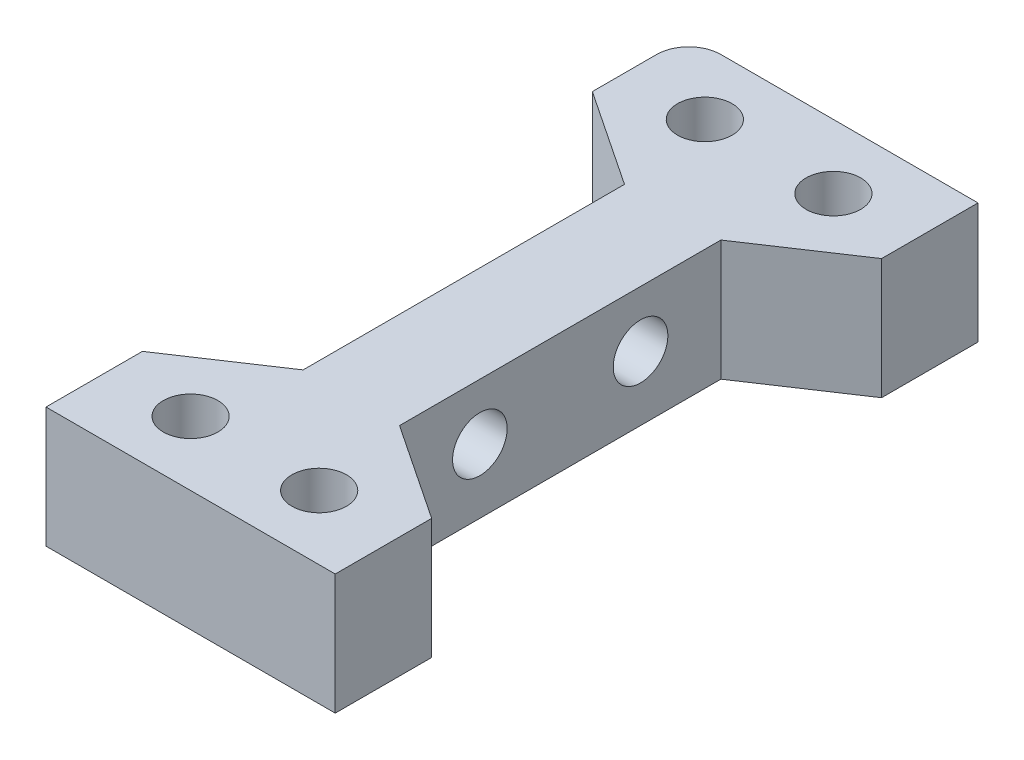
SolidWorks part; units mm, degrees
ref_plane "Front Plane" through (0, 0, 0) normal (0, 0, 1) x (1, 0, 0)
ref_plane "Top Plane" through (0, 0, 0) normal (0, 1, 0) x (1, 0, 0)
ref_plane "Right Plane" through (0, 0, 0) normal (1, 0, 0) x (0, 0, -1)
sketch "Sketch1" plane through (0, 0, 0) normal (0, 1, 0) x (1, 0, 0)
  line L0 (-3, 10) -> (-9, 14)
  line L1 (-3, -10) -> (3, -10)
  line L2 (-3, -10) -> (-3, 10)
  line L3 (-3, 10) -> (3, 10)
  line L4 (3, -10) -> (3, 10)
  line L5 (-3, -10) -> (3, 10) construction
  line L6 (-3, 10) -> (3, -10) construction
  line L7 (-9, 14) -> (-9, 20)
  line L8 (-9, 20) -> (9, 20)
  line L9 (9, 20) -> (9, 14)
  line L10 (9, 14) -> (3, 10)
  line L11 (0, 0) -> (9, 0) construction
  line L12 (9, -14) -> (3, -10)
  line L13 (9, -20) -> (9, -14)
  line L14 (-9, -20) -> (9, -20)
  line L15 (-9, -14) -> (-9, -20)
  line L16 (-3, -10) -> (3, -10)
  line L17 (-3, -10) -> (-9, -14)
  circle A0 centre (-4, 16) radius 1.7
  circle A1 centre (4, 16) radius 1.7
  circle A2 centre (4, -16) radius 1.7
  circle A3 centre (-4, -16) radius 1.7
  point P0 (0, 0)
  dimension "D8" = 3.4
  dimension "D9" = 3.4
  dimension "D1" = 6
  dimension "D2" = 20
  dimension "D3" = 4
  dimension "D4" = 4
  dimension "D5" = 6
  dimension "D6" = 6
  dimension "D7" = 6
  dimension "D10" = 8
  dimension "D11" = 4
  dimension "D12" = 4
extrude "Boss-Extrude1" add sketch "Sketch1" along normal blind 7.5 contours L1 L17 L15 L14 L13 L12 A2 A3 | L1 L4 L3 L2 | L10 L9 L8 L7 L0 L3 A1 A0
sketch "Sketch2" plane through (0, 7.5, 0) normal (0, 1, 0) x (1, 0, 0)
  line L0 (-3, 10) -> (3, 10)
  line L1 (-3, -10) -> (3, -10)
  line L12 (9, -14) -> (3, -10)
  line L13 (3, -10) -> (3, 10)
  line L14 (3, 10) -> (9, 14)
  line L15 (9, 14) -> (9, 20)
  line L16 (9, 20) -> (-9, 20)
  line L17 (-9, 20) -> (-9, 14)
  line L18 (-9, 14) -> (-3, 10)
  line L19 (-3, 10) -> (-3, -10)
  line L20 (-3, -10) -> (-9, -14)
  line L21 (-9, -14) -> (-9, -20)
  line L22 (-9, -20) -> (9, -20)
  line L23 (9, -20) -> (9, -14)
  line L24 (9, -14) -> (3, -10)
  line L25 (3, -10) -> (3, 10)
  line L26 (3, 10) -> (9, 14)
  line L27 (9, 14) -> (9, 20)
  line L28 (9, 20) -> (-9, 20)
  line L29 (-9, 20) -> (-9, 14)
  line L30 (-9, 14) -> (-3, 10)
  line L31 (-3, 10) -> (-3, -10)
  line L32 (-3, -10) -> (-9, -14)
  line L33 (-9, -14) -> (-9, -20)
  line L34 (-9, -20) -> (9, -20)
  line L35 (9, -20) -> (9, -14)
  circle M13 centre (4, -16) radius 1.7
  line M14 (9, -14) -> (3, -10)
  line M16 (3, 10) -> (9, 14)
  line M17 (9, 14) -> (9, 20)
  line M18 (9, 20) -> (-9, 20)
  line M19 (-9, 20) -> (-9, 14)
  line M20 (-9, 14) -> (-3, 10)
  line M22 (-3, -10) -> (-9, -14)
  line M23 (-9, -14) -> (-9, -20)
  line M24 (-9, -20) -> (9, -20)
  line M25 (9, -20) -> (9, -14)
  circle M26 centre (-4, -16) radius 1.7
  circle M27 centre (4, 16) radius 1.7
  circle M28 centre (-4, 16) radius 1.7
  dimension "D1" = 0
extrude "Cut-Extrude1" [suppressed] cut sketch "Sketch2" against normal blind 2 contours L0 M20 M16 M17 M18 M19 M28 M27 | L1 M22 M23 M24 M25 M14 M26 M13
sketch "Sketch3" plane through (3, 0, 0) normal (1, 0, 0) x (0, 0, -1)
  line L0 (-10, 7.5) -> (10, 7.5) construction
  circle A0 centre (-5, 4) radius 1.7
  circle A1 centre (5, 4) radius 1.7
  dimension "D1" = 3.4
  dimension "D2" = 3.4
  dimension "D3" = 10
  dimension "D4" = 5
  dimension "D5" = 3.5
extrude "Cut-Extrude2" cut sketch "Sketch3" against normal blind 6
fillet "Fillet1" radius 2 1 edges at (-9, 3.75, -20)
